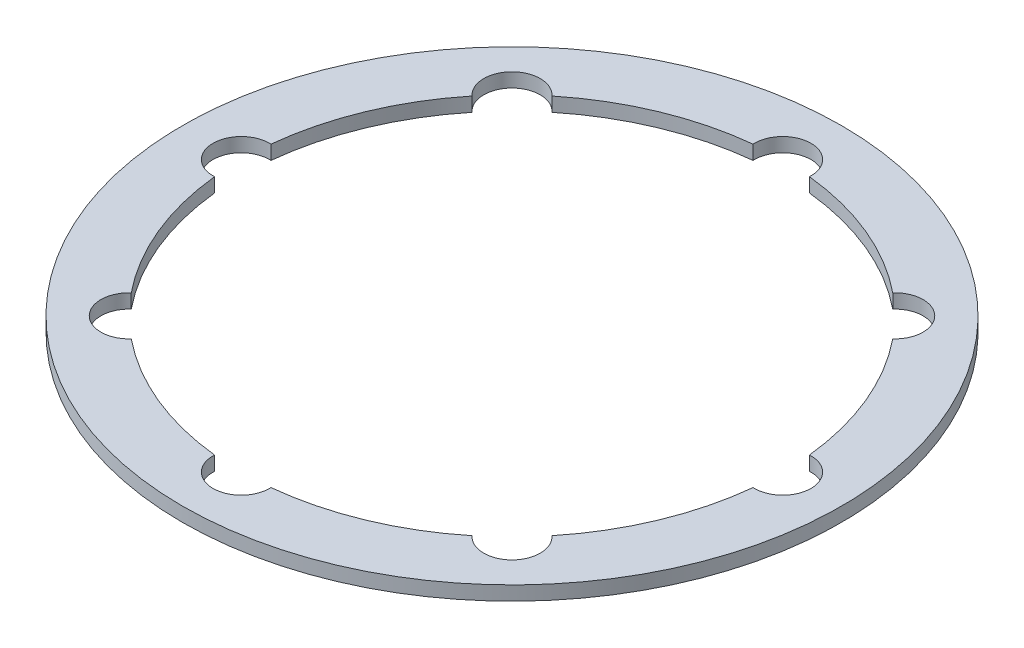
SolidWorks part; units mm, degrees
material "AISI 304"
ref_plane "Спереди" through (0, 0, 0) normal (0, 0, 1) x (1, 0, 0)
ref_plane "Сверху" through (0, 0, 0) normal (0, 1, 0) x (1, 0, 0)
ref_plane "Справа" through (0, 0, 0) normal (1, 0, 0) x (0, 0, -1)
sketch "Эскиз1" plane through (0, 0, 0) normal (0, 1, 0) x (1, 0, 0)
  line L0 (0, 0) -> (70, 0) construction
  circle A0 centre (0, 0) radius 70
  arc A2 (-5.9918, 57.187) -> (-36.2004, 44.6741) centre (0, 0) ccw
  arc A3 (57.187, -5.9918) -> (57.187, 5.9918) centre (57.5, 0) ccw
  arc A4 (36.2004, -44.6741) -> (44.6741, -36.2004) centre (40.6586, -40.6586) ccw
  arc A5 (-5.9918, -57.187) -> (5.9918, -57.187) centre (0, -57.5) ccw
  arc A6 (-44.6741, -36.2004) -> (-36.2004, -44.6741) centre (-40.6586, -40.6586) ccw
  arc A7 (-57.187, 5.9918) -> (-57.187, -5.9918) centre (-57.5, 0) ccw
  arc A8 (-36.2004, 44.6741) -> (-44.6741, 36.2004) centre (-40.6586, 40.6586) ccw
  arc A9 (5.9918, 57.187) -> (-5.9918, 57.187) centre (0, 57.5) ccw
  arc A10 (44.6741, 36.2004) -> (36.2004, 44.6741) centre (40.6586, 40.6586) ccw
  arc A11 (36.2004, 44.6741) -> (5.9918, 57.187) centre (0, 0) ccw
  arc A12 (57.187, 5.9918) -> (44.6741, 36.2004) centre (0, 0) ccw
  arc A13 (44.6741, -36.2004) -> (57.187, -5.9918) centre (0, 0) ccw
  arc A14 (5.9918, -57.187) -> (36.2004, -44.6741) centre (0, 0) ccw
  arc A15 (-36.2004, -44.6741) -> (-5.9918, -57.187) centre (0, 0) ccw
  arc A16 (-57.187, -5.9918) -> (-44.6741, -36.2004) centre (0, 0) ccw
  arc A17 (-44.6741, 36.2004) -> (-57.187, 5.9918) centre (0, 0) ccw
  dimension "D1" = 140
  dimension "D3" = 115
  dimension "D4" = 12
  dimension "D5" = 8
extrude "Бобышка-Вытянуть1" add sketch "Эскиз1" along normal blind 3
equation "\"Толщина проставки\"= 3мм"
equation "\"D1@Бобышка-Вытянуть1\"=\"Толщина проставки\""
equation "\"Диаметр отверстия\"= 12мм"
equation "\"D4@Эскиз1\"=\"Диаметр отверстия\""
